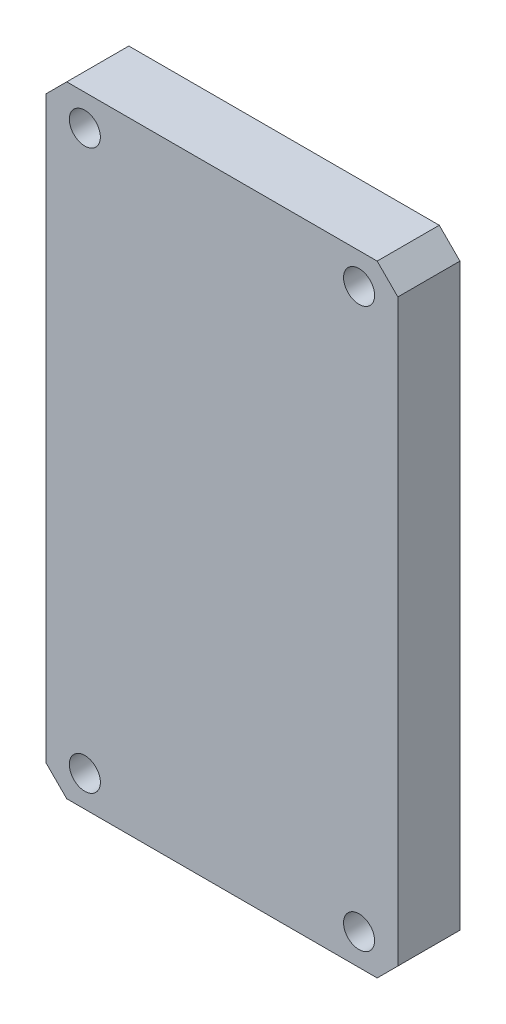
SolidWorks part; units mm, degrees
ref_plane "Front Plane" through (0, 0, 0) normal (0, 0, 1) x (1, 0, 0)
ref_plane "Top Plane" through (0, 0, 0) normal (0, 1, 0) x (1, 0, 0)
ref_plane "Right Plane" through (0, 0, 0) normal (1, 0, 0) x (0, 0, -1)
sketch "Sketch2" plane through (0, 0, 0) normal (0, 0, 1) x (1, 0, 0)
  line L1 (0, 0) -> (34, 0)
  line L2 (0, 0) -> (0, 60)
  line L3 (0, 60) -> (34, 60)
  line L4 (34, 0) -> (34, 60)
  dimension "D1" = 60
  dimension "D2" = 34
extrude "Boss-Extrude1" add sketch "Sketch2" along normal blind 6
sketch "Sketch3" plane through (0, 0, 6) normal (0, 0, 1) x (1, 0, 0)
  line L0 (0, 57) -> (34, 57) construction
  line L1 (0, 60) -> (0, 0) construction
  line L2 (34, 0) -> (34, 60) construction
  line L3 (0, 3) -> (34, 3) construction
  line L4 (3.75, 60) -> (3.75, 0) construction
  line L5 (34, 60) -> (0, 60) construction
  line L6 (0, 0) -> (34, 0) construction
  line L7 (30.25, 60) -> (30.25, 0) construction
  circle A0 centre (3.75, 57) radius 1.5
  circle A1 centre (30.25, 57) radius 1.5
  circle A2 centre (3.75, 3) radius 1.5
  circle A3 centre (30.25, 3) radius 1.5
  dimension "D1" = 3.75
  dimension "D2" = 3.75
  dimension "D3" = 3
  dimension "D4" = 3
extrude "Cut-Extrude1" cut sketch "Sketch3" against normal through all
chamfer "Chamfer1" distance 2 angle 45 4 edges at (34, 0, 3) (0, 0, 3) (0, 60, 3) (34, 60, 3)
